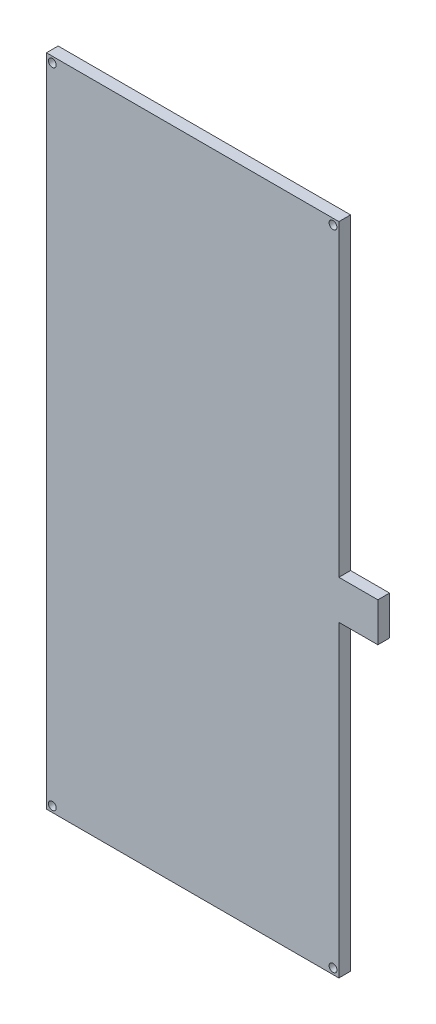
SolidWorks part; units mm, degrees
ref_plane "Front Plane" through (0, 0, 0) normal (0, 0, 1) x (1, 0, 0)
ref_plane "Top Plane" through (0, 0, 0) normal (0, 1, 0) x (1, 0, 0)
ref_plane "Right Plane" through (0, 0, 0) normal (1, 0, 0) x (0, 0, -1)
sketch "Sketch1" plane through (0, 0, 0) normal (0, 0, 1) x (1, 0, 0)
  line L1 (-37.5, -84) -> (37.5, -84)
  line L2 (-37.5, -84) -> (-37.5, 84)
  line L3 (-37.5, 84) -> (37.5, 84)
  line L4 (37.5, -84) -> (37.5, 84)
  line L5 (-37.5, -84) -> (37.5, 84) construction
  line L6 (-37.5, 84) -> (37.5, -84) construction
  point P0 (0, 0)
  dimension "D1" = 75
  dimension "D2" = 168
extrude "Boss-Extrude1" add sketch "Sketch1" along normal blind 3
sketch "Sketch2" plane through (0, 0, 3) normal (0, 0, 1) x (1, 0, 0)
  line L0 (37.5, 84) -> (36, 84)
  line L1 (37.5, 84) -> (-37.5, 84) construction
  line L2 (36, 84) -> (36, 82.5)
  line L3 (0, -121.097) -> (0, 121.097) construction
  line L4 (-106.694, 0) -> (106.694, 0) construction
  circle A0 centre (36, 82.5) radius 1
  circle A1 centre (-36, 82.5) radius 1
  circle A2 centre (36, -82.5) radius 1
  circle A3 centre (-36, -82.5) radius 1
  point P11 (0, 0)
  point P15 (0, 0)
  dimension "D1" = 1.5
  dimension "D2" = 1.5
extrude "Cut-Extrude1" cut sketch "Sketch2" against normal through all contours A0 | A1 | A3 | A2
sketch "Sketch3" plane through (0, 0, 3) normal (0, 0, 1) x (1, 0, 0)
  line L0 (37.5, -84) -> (37.5, 84) construction
  line L1 (37.5, 5) -> (47.5, 5)
  line L3 (37.5, -5) -> (47.5, -5)
  line L4 (47.5, 5) -> (47.5, -5)
  line L5 (37.5, 0) -> (47.5, -5) construction
  line L6 (37.5, 0) -> (47.5, 5) construction
  line L7 (37.5, 5) -> (37.5, -5)
  point P0 (37.5, 0)
  dimension "D1" = 10
extrude "Boss-Extrude2" add sketch "Sketch3" against normal blind 3
